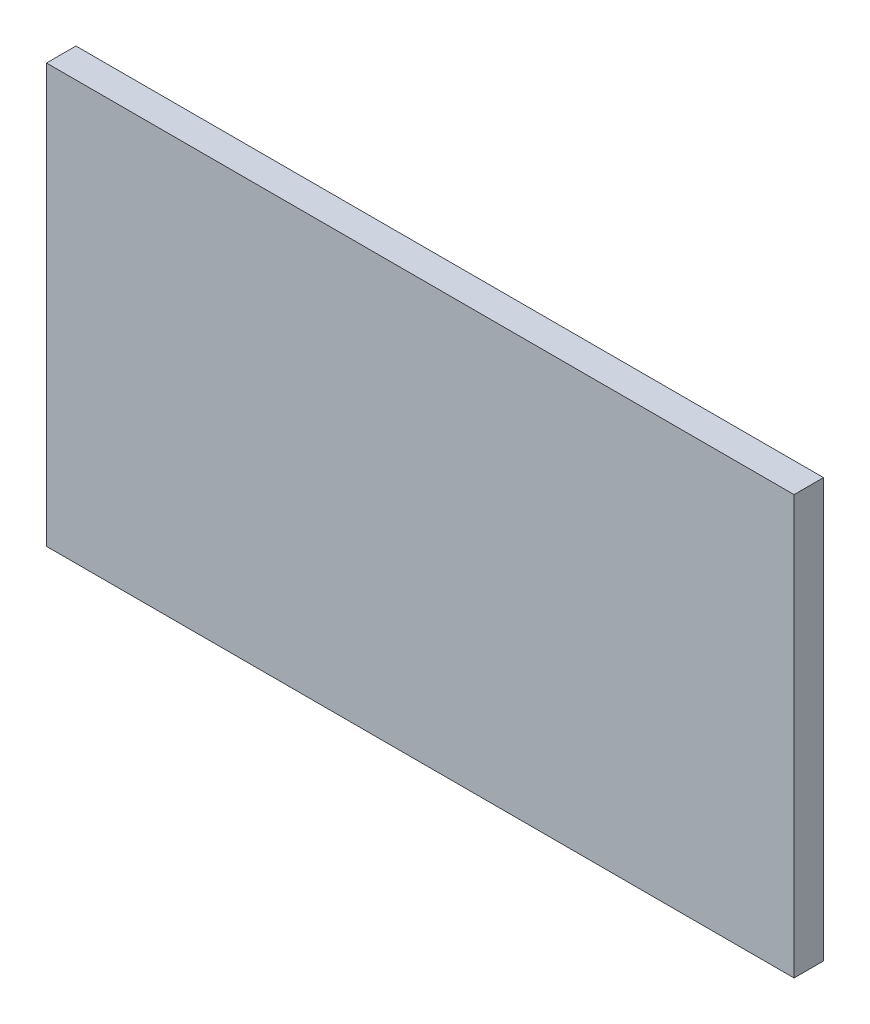
SolidWorks part; units mm, degrees
ref_plane "Alzado" through (0, 0, 0) normal (0, 0, 1) x (1, 0, 0)
ref_plane "Planta" through (0, 0, 0) normal (0, 1, 0) x (1, 0, 0)
ref_plane "Vista lateral" through (0, 0, 0) normal (1, 0, 0) x (0, 0, -1)
sketch "Croquis1" plane through (0, 0, 0) normal (0, 0, 1) x (1, 0, 0)
  line L1 (-25.4, -14.224) -> (25.4, -14.224)
  line L2 (-25.4, -14.224) -> (-25.4, 14.224)
  line L3 (-25.4, 14.224) -> (25.4, 14.224)
  line L4 (25.4, -14.224) -> (25.4, 14.224)
  line L5 (-25.4, -14.224) -> (25.4, 14.224) construction
  line L6 (-25.4, 14.224) -> (25.4, -14.224) construction
  point P0 (0, 0)
  dimension "D1" = 50.8
  dimension "D2" = 28.448
extrude "Saliente-Extruir1" add sketch "Croquis1" along normal blind 2
